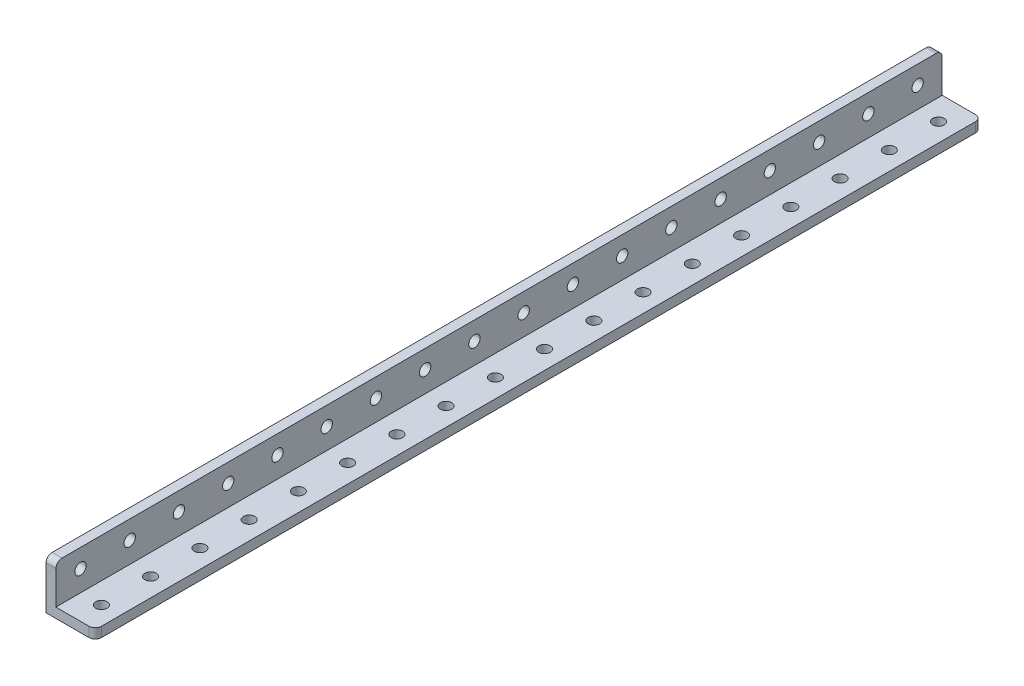
SolidWorks part; units mm, degrees
other "Defeature"
material "5052 Alloy"
ref_plane "Front Plane" through (0, 0, 0) normal (0, 0, 1) x (1, 0, 0)
ref_plane "Top Plane" through (0, 0, 0) normal (0, 1, 0) x (1, 0, 0)
ref_plane "Right Plane" through (0, 0, 0) normal (1, 0, 0) x (0, 0, -1)
sketch "Sketch1" plane through (0, 0, 0) normal (0, 0, 1) x (1, 0, 0)
  line L0 (0, 0) -> (16, 0)
  line L1 (16, 0) -> (16, 3.2)
  line L2 (16, 3.2) -> (3.2, 3.2)
  line L3 (3.2, 3.2) -> (3.2, 16)
  line L4 (3.2, 16) -> (0, 16)
  line L5 (0, 16) -> (0, 0)
  dimension "D1" = 16
  dimension "D2" = 3.2
  dimension "D3" = 16
  dimension "D4" = 3.2
extrude "Boss-Extrude1" add sketch "Sketch1" against normal mid plane 288
sketch "Sketch2" plane through (0, 0, 0) normal (-1, 0, 0) x (0, 0, 1)
  line L5 (-144, 16) -> (144, 16) construction
  line L8 (144, 3.2) -> (144, 16) construction
  circle A12 centre (136, 10) radius 1.85
  point P8 (144, 9.6)
  dimension "D1" = 3.7
  dimension "D2" = 6
  dimension "D3" = 8
extrude "Cut-Extrude1" cut sketch "Sketch2" against normal through all
sketch "Sketch3" plane through (0, 3.2, 0) normal (0, 1, 0) x (1, 0, 0)
  line L0 (16, 144) -> (16, -144) construction
  line L1 (16, -144) -> (3.2, -144) construction
  circle A0 centre (10, -136) radius 1.85
  dimension "D3" = 3.7
  dimension "D1" = 6
  dimension "D2" = 8
extrude "Cut-Extrude2" cut sketch "Sketch3" against normal up to next
pattern_linear "LPattern1" count 18 spacing 16 along (0, 0, -1) of "Cut-Extrude1", "Cut-Extrude2"
fillet "Fillet1" radius 2 4 edges at (1.6, 16, 144) (16, 1.6, 144) (16, 1.6, -144) (1.6, 16, -144)
